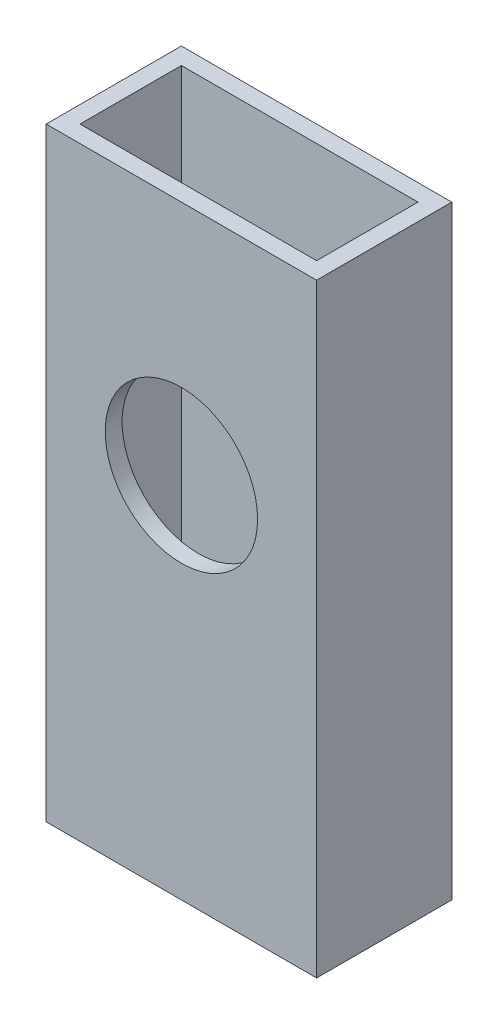
SolidWorks part; units mm, degrees
material "6063-T1"
ref_plane "Front Plane" through (0, 0, 0) normal (0, 0, 1) x (1, 0, 0)
ref_plane "Top Plane" through (0, 0, 0) normal (0, 1, 0) x (1, 0, 0)
ref_plane "Right Plane" through (0, 0, 0) normal (1, 0, 0) x (0, 0, -1)
sketch "Sketch1" plane through (0, 0, 0) normal (0, 0, 1) x (1, 0, 0)
  line L1 (-25.4, 56.769) -> (25.4, 56.769)
  line L2 (-25.4, 56.769) -> (-25.4, -56.769)
  line L3 (-25.4, -56.769) -> (25.4, -56.769)
  line L4 (25.4, 56.769) -> (25.4, -56.769)
  line L5 (-25.4, 56.769) -> (25.4, -56.769) construction
  line L6 (-25.4, -56.769) -> (25.4, 56.769) construction
  point P0 (0, 0)
  dimension "D1" = 50.8
  dimension "D2" = 113.538
extrude "Boss-Extrude1" add sketch "Sketch1" along normal blind 25.4
shell "Shell1" thickness 3.175
sketch "Sketch2" plane through (0, 0, 25.4) normal (0, 0, 1) x (1, 0, 0)
  line L0 (25.4, 56.769) -> (-25.4, 56.769) construction
  circle A0 centre (0, 12.319) radius 14.3129
  dimension "D1" = 28.6258
  dimension "D2" = 44.45
extrude "Cut-Extrude1" cut sketch "Sketch2" against normal up to vertex (25.4 mm away) up to point (0, 0, 0)
